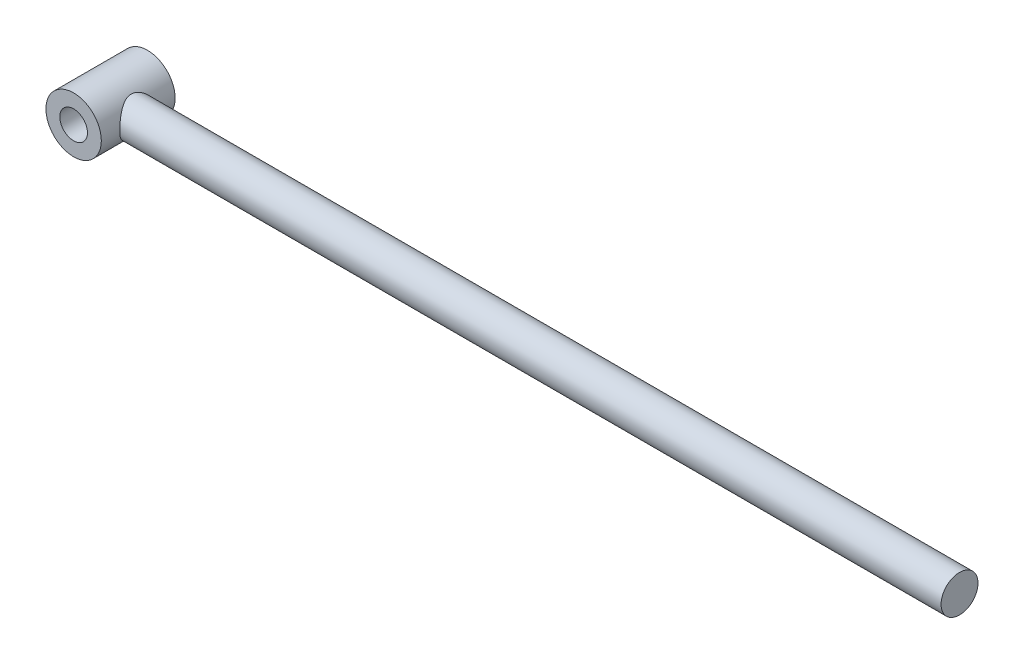
SolidWorks part; units mm, degrees
ref_plane "Front Plane" through (0, 0, 0) normal (0, 0, 1) x (1, 0, 0)
ref_plane "Top Plane" through (0, 0, 0) normal (0, 1, 0) x (1, 0, 0)
ref_plane "Right Plane" through (0, 0, 0) normal (1, 0, 0) x (0, 0, -1)
sketch "Sketch1" plane through (0, 0, 0) normal (0, 0, 1) x (1, 0, 0)
  circle A0 centre (0, 0) radius 15
  circle A1 centre (0, 0) radius 30
  dimension "D1" = 30
  dimension "D2" = 15
extrude "Boss-Extrude1" add sketch "Sketch1" along normal mid plane 80
ref_plane "Plane1" through (20, 0, 0) normal (1, 0, 0) x (0, 0, -1)
sketch "Sketch3" plane through (20, 0, 0) normal (1, 0, 0) x (0, 0, -1)
  circle A0 centre (0, 0) radius 20
  dimension "D1" = 40
extrude "Boss-Extrude2" add sketch "Sketch3" along normal blind 900
